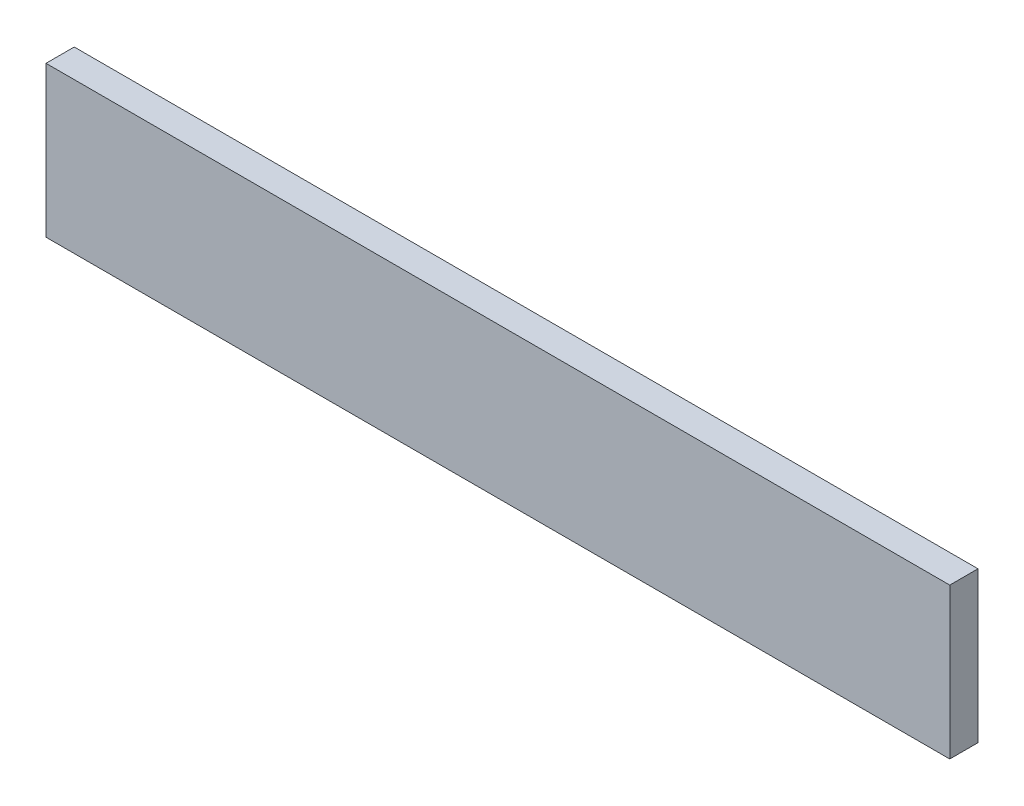
SolidWorks part; units mm, degrees
ref_plane "Front Plane" through (0, 0, 0) normal (0, 0, 1) x (1, 0, 0)
ref_plane "Top Plane" through (0, 0, 0) normal (0, 1, 0) x (1, 0, 0)
ref_plane "Right Plane" through (0, 0, 0) normal (1, 0, 0) x (0, 0, -1)
sketch "Sketch1" plane through (0, 0, 0) normal (0, 0, 1) x (1, 0, 0)
  line L1 (0, 0) -> (304.8, 0)
  line L2 (0, 0) -> (0, 50.8)
  line L3 (0, 50.8) -> (304.8, 50.8)
  line L4 (304.8, 0) -> (304.8, 50.8)
  dimension "D1" = 304.8
  dimension "D2" = 50.8
extrude "Boss-Extrude1" add sketch "Sketch1" along normal blind 9.525
